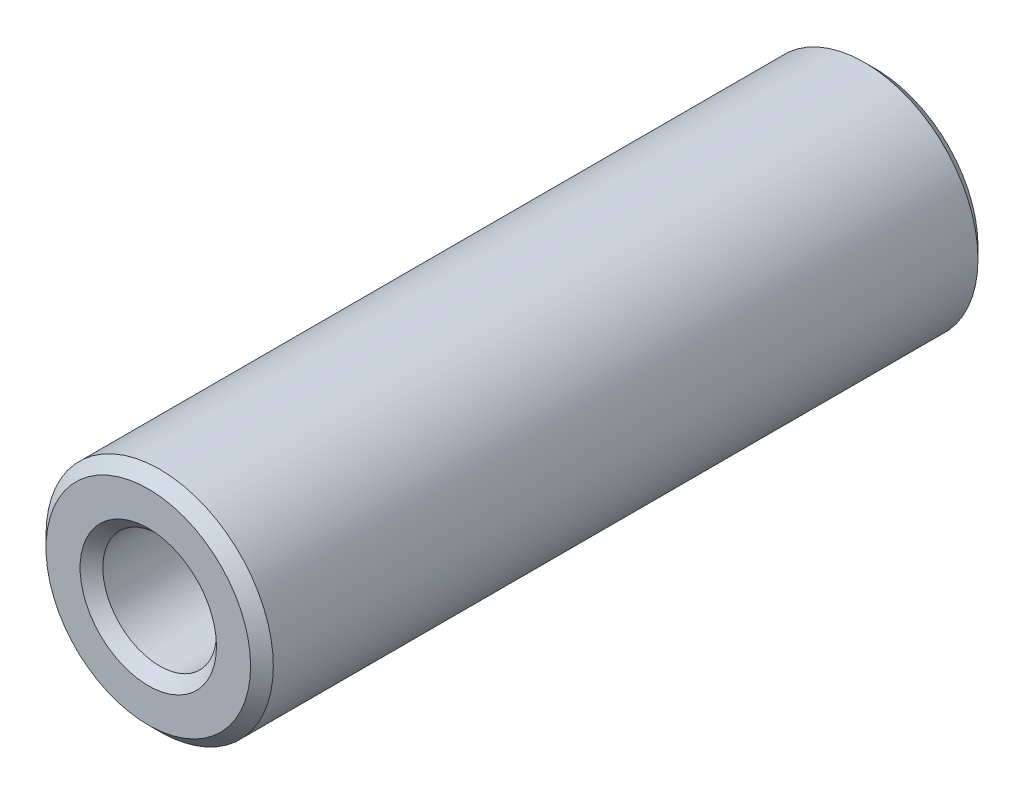
SolidWorks part; units mm, degrees
material "AISI 4140 Steel, quenched & tempered"
ref_plane "Front Plane" through (0, 0, 0) normal (1, 0, 0) x (0, 1, 0)
ref_plane "Top Plane" through (0, 0, 0) normal (0, 0, 1) x (0, 1, 0)
ref_plane "Right Plane" through (0, 0, 0) normal (0, 1, 0) x (-1, 0, 0)
sketch "Sketch1" plane through (0, 0, 0) normal (0, 0, 1) x (0, 1, 0)
  circle A0 centre (0, 0) radius 5
  circle A1 centre (0, 0) radius 2.5
  dimension "D1" = 10
  dimension "D2" = 5
extrude "Boss-Extrude1" add sketch "Sketch1" along normal mid plane 32
chamfer "Chamfer1" distance 0.5 angle 45 4 edges at (5, 0, -16) (5, 0, 16) (2.5, 0, -16) (2.5, 0, 16)
